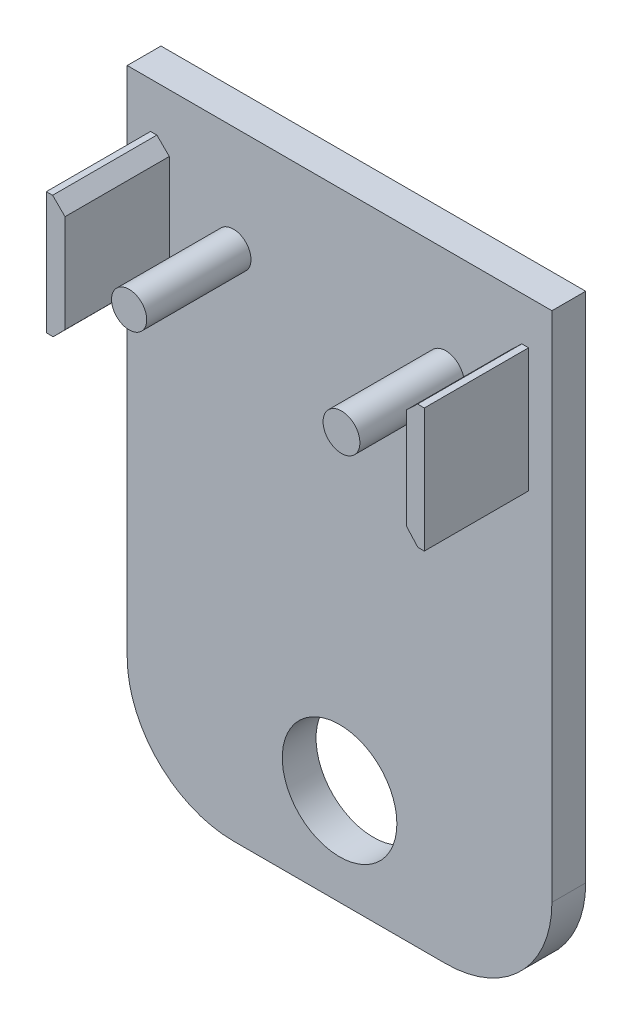
SolidWorks part; units mm, degrees
ref_plane "Front Plane" through (0, 0, 0) normal (0, 0, 1) x (1, 0, 0)
ref_plane "Top Plane" through (0, 0, 0) normal (0, 1, 0) x (1, 0, 0)
ref_plane "Right Plane" through (0, 0, 0) normal (1, 0, 0) x (0, 0, -1)
sketch "Sketch1" plane through (0, 0, 0) normal (0, 0, 1) x (1, 0, 0)
  line L0 (-76, 0) -> (-70.3, 0) construction
  line L1 (-37, -58.2595) -> (-77, -58.2595)
  line L3 (-37, -58.2595) -> (-37, 0)
  line L5 (-37, 0) -> (-77, 0)
  line L6 (-77, -58.2595) -> (-77, 0)
  line L7 (-37, -58.2595) -> (-77, 0) construction
  line L8 (-37, 0) -> (-77, -58.2595) construction
  line L9 (-77, -17.125) -> (-77, -13.3) construction
  line L10 (-37, -13.3) -> (-37, -17.125) construction
  circle A0 centre (-57, -49.15) radius 5.3964
  point P0 (-57, -29.1297)
extrude "Boss-Extrude1" add sketch "Sketch1" against normal blind 3.18 from vertex at -18.3437
fillet "Fillet1" radius 10 2 edges at (-37, -58.2595, -19.9337) (-77, -58.2595, -19.9337)
sketch "Sketch2" plane through (0, 0, -21.5237) normal (0, 0, -1) x (-1, 0, 0)
  line L0 (74.8007, -15.7965) -> (74.8007, -4.2787)
  line L1 (74.8007, -4.2787) -> (74.2072, -4.2787)
  line L2 (74.2072, -4.2787) -> (73.0356, -5.4379)
  line L3 (73.0356, -5.4379) -> (73.0356, -14.6633)
  line L4 (39.1985, -15.7965) -> (39.1985, -4.1224)
  line L5 (39.1985, -4.1224) -> (39.8364, -4.1224)
  line L6 (39.8364, -4.1224) -> (40.8708, -5.1119)
  line L7 (40.8708, -5.1119) -> (40.8708, -14.6185)
  line L8 (39.1985, -15.7965) -> (39.8071, -15.7965)
  line L9 (39.8071, -15.7965) -> (40.8708, -14.6185)
  line L10 (73.0356, -14.6633) -> (74.1568, -15.7965)
  line L11 (74.1568, -15.7965) -> (74.8007, -15.7965)
  circle A0 centre (47, -10) radius 1.735
  circle A1 centre (67.0004, -10.0004) radius 1.6568
extrude "Boss-Extrude2" add sketch "Sketch2" against normal blind 13
